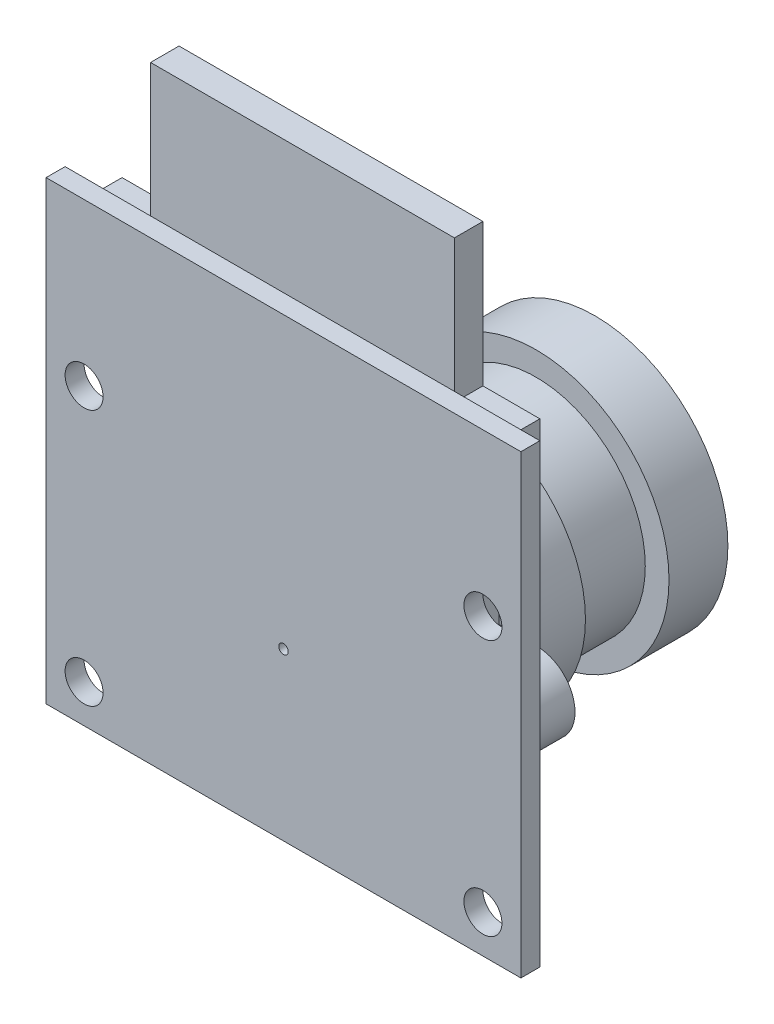
SolidWorks part; units mm, degrees
ref_plane "Спереди" through (0, 0, 0) normal (0, 0, 1) x (1, 0, 0)
ref_plane "Сверху" through (0, 0, 0) normal (0, 1, 0) x (1, 0, 0)
ref_plane "Справа" through (0, 0, 0) normal (1, 0, 0) x (0, 0, -1)
ref_plane "Плоскость4" through (0, 0, -1) normal (0, 0, -1) x (-1, 0, 0)
sketch "Эскиз1" plane through (0, 0, -1) normal (0, 0, -1) x (-1, 0, 0)
  line L0 (-25, 0) -> (0, 0)
  line L1 (0, 0) -> (0, 24)
  line L2 (0, 24) -> (-25, 24)
  line L3 (-25, 24) -> (-25, 0)
extrude "плата" add sketch "Эскиз1" against normal blind 1
sketch "Эскиз2" plane through (0, 0, -1) normal (0, 0, -1) x (-1, 0, 0)
  line L0 (-5.95, 10.75) -> (-3.95, 10.75)
  line L1 (-3.95, 6.75) -> (-5.95, 6.75)
  line L2 (-5.95, 6.75) -> (-5.95, 2.2)
  line L3 (-5.95, 2.2) -> (-19.05, 2.2)
  line L4 (-19.05, 2.2) -> (-19.05, 6.75)
  line L5 (-19.05, 6.75) -> (-21.05, 6.75)
  line L6 (-21.05, 10.75) -> (-19.05, 10.75)
  line L7 (-19.05, 10.75) -> (-19.05, 15.3)
  line L8 (-19.05, 15.3) -> (-5.95, 15.3)
  line L9 (-5.95, 15.3) -> (-5.95, 10.75)
  arc A0 (-3.95, 10.75) -> (-3.95, 6.75) centre (-3.95, 8.75) cw
  arc A1 (-21.05, 6.75) -> (-21.05, 10.75) centre (-21.05, 8.75) cw
extrude "выступ" add sketch "Эскиз2" along normal blind 3.8
sketch "Эскиз3" plane through (0, 0, -1) normal (0, 0, -1) x (-1, 0, 0)
  line L0 (-23.5, 18.6977) -> (-23.5, 23.5)
  line L1 (-23.5, 23.5) -> (-1.5, 23.5)
  line L2 (-1.5, 23.5) -> (-1.5, 18.6977)
  line L3 (-1.5, 18.6977) -> (-23.5, 18.6977)
extrude "разъем шлейфа" add sketch "Эскиз3" along normal blind 1.5
ref_plane "Плоскость5" through (0, 8.75, 0) normal (0, -1, 0) x (1, 0, 0)
sketch "Эскиз4" plane through (0, 8.75, 0) normal (0, -1, 0) x (1, 0, 0)
  line L0 (19.1, -4.8) -> (12.5, -4.8)
  line L1 (12.5, -4.8) -> (12.5, -16.4)
  line L2 (12.5, -16.4) -> (19.5, -16.4)
  line L3 (19.5, -16.4) -> (19.5, -13.3)
  line L4 (19.5, -13.3) -> (18.25, -13.3)
  line L5 (18.25, -13.3) -> (18.25, -9.3)
  line L6 (18.25, -9.3) -> (19.1, -9.3)
  line L7 (19.1, -9.3) -> (19.1, -4.8)
  line L8 (12.5, -4.8) -> (12.5, -16.4) construction
revolve "объектив" add sketch "Эскиз4" angle 360 about L8
hole_wizard "маленьекое отверстие" positions "Эскиз6" profile "Эскиз5" hole size "Ø0.5" standard "Ansi Metric"
sketch "Эскиз6" plane through (0, 0, 0) normal (0, 0, 1) x (1, 0, 0)
  point P0 (12.5, 8.75)
sketch "Эскиз5" plane through (12.5, 8.75, 0) normal (1, 0, 0) x (0, -1, 0)
  line L0 (0, 0) -> (0, 1)
  line L1 (0, 1) -> (0.25, 1)
  line L2 (0.25, 1) -> (0.25, 0)
  line L5 (0.25, 0) -> (0, 0)
  line L10 (0, 1) -> (-0.25, 1) construction
  line L11 (0, -6.35) -> (0, 107.95) construction
  dimension "Диаметр отверстия" = 0.5
  dimension "Глубина отверстия" = 1
  dimension "Угол заточки сверла" = 180
hole_wizard "крепежные отверстия" positions "Эскиз8" profile "Эскиз7" hole size "Ø2.0" standard "Ansi Metric"
sketch "Эскиз8" plane through (0, 0, 0) normal (0, 0, 1) x (1, 0, 0)
  point P0 (2, 2)
  point P1 (2, 15.5)
  point P2 (23, 15.5)
  point P3 (23, 2)
sketch "Эскиз7" plane through (2, 2, 0) normal (1, 0, 0) x (0, -1, 0)
  line L0 (0, 0) -> (0, 16.4)
  line L1 (0, 16.4) -> (1, 16.4)
  line L2 (1, 16.4) -> (1, 0)
  line L5 (1, 0) -> (0, 0)
  line L11 (0, -6.35) -> (0, 107.95) construction
  dimension "Диаметр сквозного отверстия" = 2
  dimension "Глубина сквозного отверстия" = 16.4
sketch "Эскиз10" plane through (0, 0, 0) normal (0, 0, 1) x (1, 0, 0)
  line L1 (23, 2) -> (2, 2)
  line L2 (23, 2) -> (23, 15.5)
  line L3 (23, 15.5) -> (2, 15.5)
  line L4 (2, 2) -> (2, 15.5)
  line L5 (23, 2) -> (2, 15.5) construction
  line L6 (23, 15.5) -> (2, 2) construction
  point P0 (12.5, 8.75)
  dimension "D1" = 21
  dimension "D2" = 13.5
  dimension "D3" = 6.75
ref_plane "Плоскость6" through (0, 8.75, 0) normal (0, 1, 0) x (1, 0, 0)
sketch "Эскиз11" plane through (0, 8.75, 0) normal (0, 1, 0) x (1, 0, 0)
  line L0 (5.5, 16.4) -> (-334.7769, 76.4)
  line L1 (19.5, 16.4) -> (359.7769, 76.4)
  line L2 (-334.7769, 76.4) -> (359.7769, 76.4)
  line L3 (19.5, 16.4) -> (5.5, 16.4) construction
  dimension "D1" = 160
  dimension "D2" = 60
sketch "Эскиз12" plane through (0, 23.5, 0) normal (0, 1, 0) x (1, 0, 0)
  line L0 (1.5, 2.5) -> (23.5, 2.5) construction
  line L1 (4.5, 2.5) -> (20.5, 2.5)
  line L2 (4.5, 2.5) -> (4.5, 1)
  line L3 (4.5, 1) -> (20.5, 1)
  line L4 (20.5, 2.5) -> (20.5, 1)
  line L5 (0, 1) -> (25, 1) construction
  point P8 (12.0731, 2.5)
  point P9 (12.5, 2.5)
  point P10 (12.5, 2.5)
  dimension "D1" = 16
extrude "Шлейф" add sketch "Эскиз12" along normal blind 7.5
